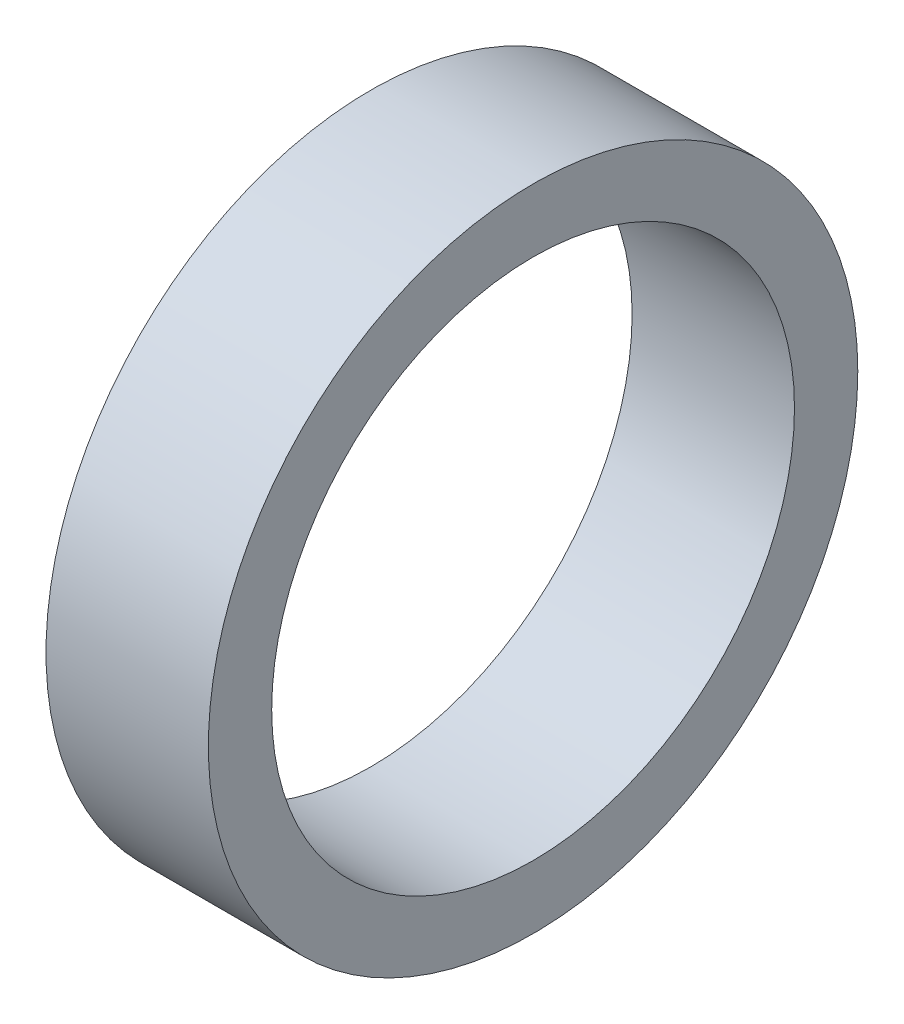
SolidWorks part; units mm, degrees
ref_plane "Front Plane" through (0, 0, 0) normal (0, 0, 1) x (1, 0, 0)
ref_plane "Top Plane" through (0, 0, 0) normal (0, 1, 0) x (1, 0, 0)
ref_plane "Right Plane" through (0, 0, 0) normal (1, 0, 0) x (0, 0, -1)
sketch "Sketch1" plane through (0, 0, 0) normal (1, 0, 0) x (0, 0, -1)
  circle A0 centre (0, 0) radius 4.025
  circle A1 centre (0, 0) radius 5
  dimension "D1" = 8.05
  dimension "D2" = 10
extrude "Boss-Extrude1" add sketch "Sketch1" along normal blind 2.5
